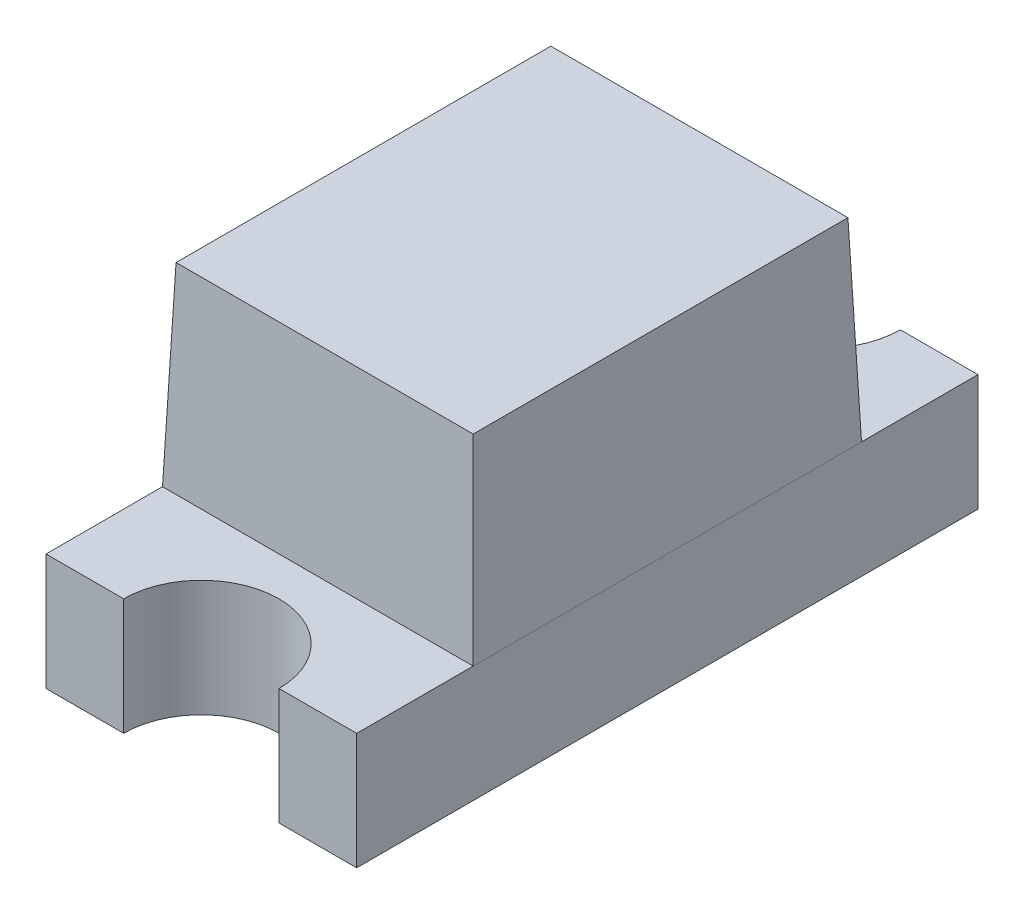
SolidWorks part; units mm, degrees
ref_plane "Piano frontale" through (0, 0, 0) normal (0, 0, 1) x (1, 0, 0)
ref_plane "Piano superiore" through (0, 0, 0) normal (0, 1, 0) x (1, 0, 0)
ref_plane "Piano destro" through (0, 0, 0) normal (1, 0, 0) x (0, 0, -1)
sketch "Schizzo1" plane through (0, 0, 0) normal (0, 1, 0) x (1, 0, 0)
  line L0 (0.4, 1.6) -> (0.4, 0) construction
  line L1 (0.8, 1.6) -> (0.6, 1.6)
  line L2 (0, 0) -> (0, 1.6)
  line L3 (0, 1.6) -> (0.2, 1.6)
  line L4 (0.8, 0) -> (0.8, 1.6)
  line L5 (0.2, 1.6) -> (0.6, 1.6) construction
  line L6 (0, 0.8) -> (0.8, 0.8) construction
  line L7 (0, 0) -> (0.2, 0)
  line L8 (0.8, 0) -> (0.6, 0)
  arc A0 (0.2, 1.6) -> (0.6, 1.6) centre (0.4, 1.6) ccw
  arc A1 (0.2, 0) -> (0.6, 0) centre (0.4, 0) cw
  dimension "D1" = 0.8
  dimension "D2" = 1.6
  dimension "D3" = 0.2
  dimension "D4" = 0.2
extrude "Estrusione-Estrusione1" add sketch "Schizzo1" along normal blind 0.3
sketch "Schizzo2" plane through (0, 0.3, 0) normal (0, 1, 0) x (1, 0, 0)
  circle A0 centre (0.0925, 1.3827) radius 0.05
extrude "Taglio-Estrusione1" cut sketch "Schizzo2" against normal blind 0.05
sketch "Schizzo3" plane through (0, 0.3, 0) normal (0, 1, 0) x (1, 0, 0)
  line L0 (0.8, 0.8) -> (0, 0.8) construction
  line L1 (0.8, 0) -> (0.8, 1.6) construction
  line L2 (0, 1.6) -> (0, 0) construction
  line L4 (0, 1.3) -> (0.8, 1.3)
  line L5 (0, 1.3) -> (0, 0.3)
  line L6 (0, 0.3) -> (0.8, 0.3)
  line L7 (0.8, 1.3) -> (0.8, 0.3)
  dimension "D1" = 0.5
  dimension "D2" = 0.5
extrude "Estrusione-Estrusione2" add sketch "Schizzo3" along normal blind 0.5 draft 2
